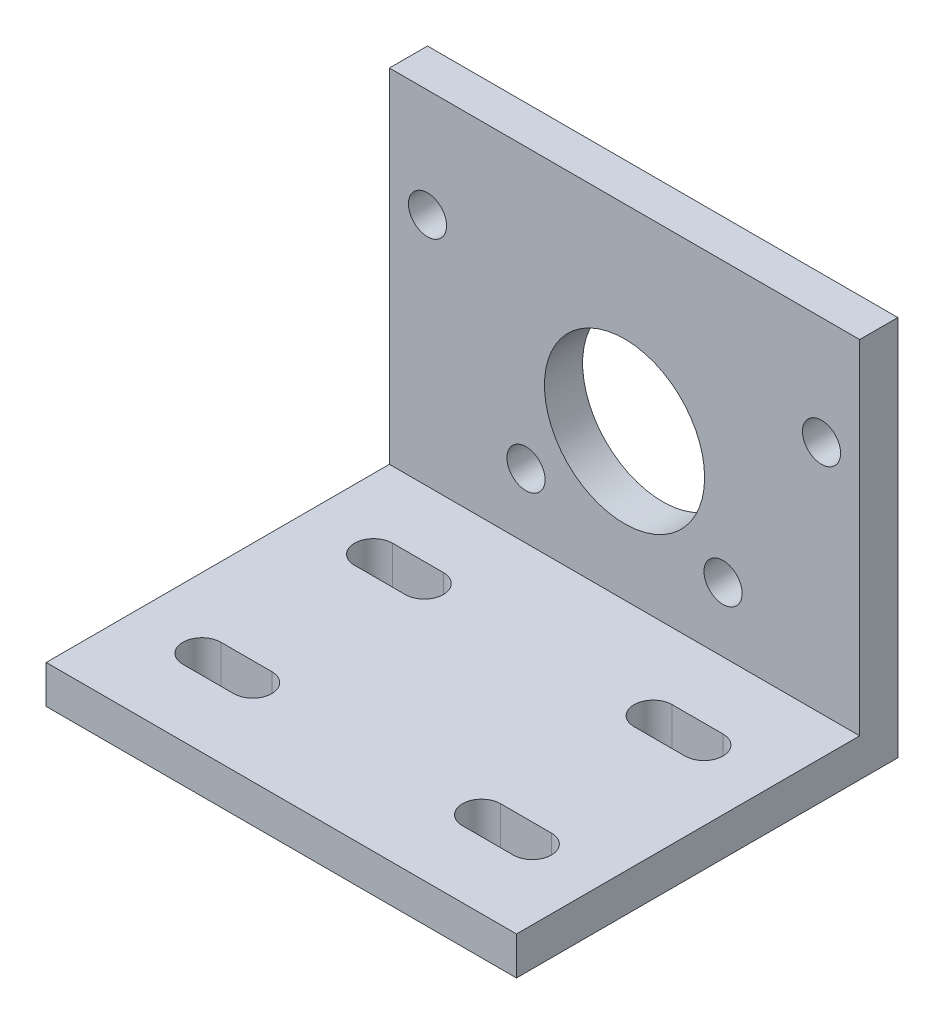
SolidWorks part; units mm, degrees
ref_plane "Front Plane" through (0, 0, 0) normal (0, 0, 1) x (1, 0, 0)
ref_plane "Top Plane" through (0, 0, 0) normal (0, 1, 0) x (1, 0, 0)
ref_plane "Right Plane" through (0, 0, 0) normal (1, 0, 0) x (0, 0, -1)
sketch "Sketch1" plane through (0, 0, 0) normal (0, 0, 1) x (1, 0, 0)
  line L0 (3, 21.5) -> (34, 21.5) construction
  line L1 (0, 0) -> (37, 0)
  line L2 (0, 0) -> (0, 30)
  line L3 (0, 30) -> (37, 30)
  line L4 (37, 0) -> (37, 30)
  line L5 (0, 0) -> (37, 0)
  line L6 (0, 0) -> (0, 3)
  line L7 (0, 3) -> (37, 3)
  line L8 (37, 0) -> (37, 3)
  line L9 (10.75, 8.0766) -> (18.5, 21.5) construction
  line L10 (18.5, 21.5) -> (26.25, 8.0766) construction
  circle A0 centre (18.5, 14.5) radius 6.3
  circle A1 centre (10.75, 8.0766) radius 1.5
  circle A2 centre (3, 21.5) radius 1.5
  circle A3 centre (26.25, 8.0766) radius 1.5
  circle A4 centre (34, 21.5) radius 1.5
  arc A5 (2.0683, 30) -> (34.9317, 30) centre (18.5, 21.5) ccw construction
  dimension "D2" = 12.6
  dimension "D3" = 3
  dimension "D5" = 37
  dimension "D10" = 18.5
  dimension "D1" = 15.5
  dimension "D4" = 31
  dimension "D6" = 18.5
  dimension "D7" = 3
  dimension "D8" = 60
  dimension "D9" = 60
  dimension "D11" = 11.5
  dimension "D12" = 15.5
  dimension "D13" = 27
extrude "Boss-Extrude2" add sketch "Sketch1" along normal blind 3 contours L2 L7 L4 L3 A4 A3 A2 A1 A0
sketch "Sketch2" plane through (0, 0, 3) normal (0, 0, 1) x (1, 0, 0)
  line L0 (37, 3) -> (37, 30) construction
  line L1 (0, 3) -> (37, 3)
  line L2 (0, 3) -> (0, 0)
  line L3 (0, 0) -> (37, 0)
  line L4 (37, 3) -> (37, 0)
  dimension "D1" = 3
extrude "Boss-Extrude4" add sketch "Sketch2" along normal blind 27 and the other way blind 3
sketch "Sketch4" plane through (0, 3, 0) normal (0, 1, 0) x (1, 0, 0)
  line L0 (5.5, -9.75) -> (9.5, -9.75) construction
  line L1 (5.5, -8.25) -> (9.5, -8.25)
  line L2 (5.5, -11.25) -> (9.5, -11.25)
  line L3 (27.5, -9.75) -> (31.5, -9.75) construction
  line L4 (27.5, -8.25) -> (31.5, -8.25)
  line L5 (27.5, -11.25) -> (31.5, -11.25)
  line L6 (5.5, -23.25) -> (9.5, -23.25) construction
  line L9 (27.5, -23.25) -> (31.5, -23.25) construction
  line L10 (27.5, -21.75) -> (31.5, -21.75)
  line L11 (27.5, -24.75) -> (31.5, -24.75)
  line L12 (5.5, -21.75) -> (9.5, -21.75)
  line L13 (5.5, -24.75) -> (9.5, -24.75)
  line L14 (0, -3) -> (37, -3) construction
  line L16 (0, -3) -> (0, -30) construction
  arc A0 (5.5, -8.25) -> (5.5, -11.25) centre (5.5, -9.75) ccw
  arc A1 (9.5, -11.25) -> (9.5, -8.25) centre (9.5, -9.75) ccw
  arc A2 (27.5, -8.25) -> (27.5, -11.25) centre (27.5, -9.75) ccw
  arc A3 (31.5, -11.25) -> (31.5, -8.25) centre (31.5, -9.75) ccw
  arc A6 (27.5, -21.75) -> (27.5, -24.75) centre (27.5, -23.25) ccw
  arc A7 (31.5, -24.75) -> (31.5, -21.75) centre (31.5, -23.25) ccw
  arc A8 (5.5, -21.75) -> (5.5, -24.75) centre (5.5, -23.25) ccw
  arc A9 (9.5, -24.75) -> (9.5, -21.75) centre (9.5, -23.25) ccw
  point P2 (7.5, -9.75)
  point P7 (29.5, -9.75)
  point P16 (7.5, -23.25)
  point P21 (29.5, -23.25)
  dimension "D3" = 1.5
  dimension "D1" = 13.5
  dimension "D2" = 18
  dimension "D4" = 4
  dimension "D5" = 6.75
  dimension "D6" = 7.5
extrude "Cut-Extrude1" cut sketch "Sketch4" against normal through all
sketch "Croquis1" plane through (0, 3, 0) normal (0, 1, 0) x (1, 0, 0)
  line L0 (0, -3) -> (37, -3) construction
  line L1 (31, -3) -> (21.6671, -3)
  line L2 (31, -3) -> (31, -30)
  line L3 (31, -30) -> (21.6671, -30)
  line L4 (21.6671, -3) -> (21.6671, -30)
  line L5 (37, -30) -> (0, -30) construction
  point P8 (18.5, -30)
  dimension "D1" = 12.5
extrude "Saliente-Extruir1" add sketch "Croquis1" along normal blind 10
sketch "Croquis2" plane through (0, 3, 0) normal (0, 1, 0) x (1, 0, 0)
  line L1 (21.6671, -3) -> (31, -3)
  line L2 (21.6671, -3) -> (21.6671, -30)
  line L3 (21.6671, -30) -> (31, -30)
  line L4 (31, -3) -> (31, -30)
extrude "Cortar-Extruir1" cut sketch "Croquis2" along normal blind 10
sketch "Croquis3" plane through (0, 3, 0) normal (0, 1, 0) x (1, 0, 0)
  line L0 (0, -3) -> (37, -3) construction
  line L1 (20.6181, -3) -> (31, -3)
  line L2 (20.6181, -3) -> (20.6181, -30)
  line L3 (20.6181, -30) -> (31, -30)
  line L4 (31, -3) -> (31, -30)
  line L5 (37, -30) -> (0, -30) construction
  point P8 (18.5, -30)
  dimension "D1" = 12.5
extrude "Saliente-Extruir2" add sketch "Croquis3" along normal blind 10
sketch "Croquis4" plane through (0, 3, 0) normal (0, 1, 0) x (1, 0, 0)
  line L1 (20.6181, -3) -> (31, -3)
  line L2 (20.6181, -3) -> (20.6181, -30)
  line L3 (20.6181, -30) -> (31, -30)
  line L4 (31, -3) -> (31, -30)
extrude "Cortar-Extruir3" cut sketch "Croquis4" along normal blind 10
sketch "Croquis5" plane through (0, 3, 0) normal (0, 1, 0) x (1, 0, 0)
  line L0 (0, -3) -> (37, -3) construction
  line L1 (21.8758, -3) -> (31, -3)
  line L2 (21.8758, -3) -> (21.8758, -30)
  line L3 (21.8758, -30) -> (31, -30)
  line L4 (31, -3) -> (31, -30)
  line L5 (37, -30) -> (0, -30) construction
  point P8 (18.5, -30)
  dimension "D1" = 12.5
extrude "Saliente-Extruir3" add sketch "Croquis5" along normal blind 10
sketch "Croquis6" plane through (0, 3, 0) normal (0, 1, 0) x (1, 0, 0)
  line L1 (21.8758, -3) -> (31, -3)
  line L2 (21.8758, -3) -> (21.8758, -30)
  line L3 (21.8758, -30) -> (31, -30)
  line L4 (31, -3) -> (31, -30)
extrude "Cortar-Extruir5" cut sketch "Croquis6" along normal blind 10
